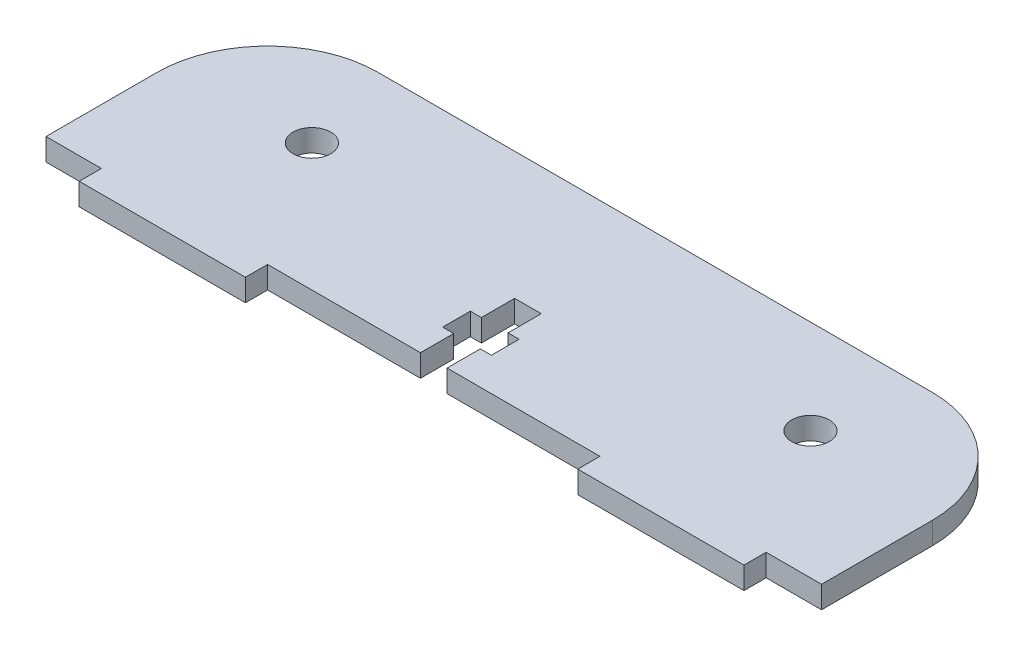
SolidWorks part; units mm, degrees
material "Thornel Mat VMA"
ref_plane "前视基准面" through (0, 0, 0) normal (0, 0, 1) x (1, 0, 0)
ref_plane "上视基准面" through (0, 0, 0) normal (0, 1, 0) x (1, 0, 0)
ref_plane "右视基准面" through (0, 0, 0) normal (1, 0, 0) x (0, 0, -1)
sketch "草图1" plane through (0, 0, 0) normal (0, 1, 0) x (1, 0, 0)
  line L1 (0, 0) -> (70, 0)
  line L2 (0, 0) -> (0, -20)
  line L3 (0, -20) -> (70, -20)
  line L4 (70, 0) -> (70, -20)
  line L5 (0, 0) -> (70, -20) construction
  line L6 (0, -20) -> (70, 0) construction
  circle A0 centre (57.5, -8.5) radius 1.7
  circle A1 centre (12.5, -8.5) radius 1.7
  point P4 (35, -10)
  dimension "D2" = 3.4
  dimension "D3" = 3.4
  dimension "D4" = 11.5
  dimension "D5" = 11.5
  dimension "D6" = 22.5
  dimension "D7" = 22.5
  dimension "D1" = 20
  dimension "D8" = 70
extrude "凸台-拉伸1" add sketch "草图1" along normal blind 2
sketch "草图2" plane through (0, 2, 0) normal (0, 1, 0) x (1, 0, 0)
  line L0 (33.8, -20) -> (33.8, -17)
  line L1 (0, -20) -> (70, -20) construction
  line L2 (33.8, -17) -> (32.8, -17)
  line L3 (32.8, -17) -> (32.8, -14.5)
  line L4 (32.8, -14.5) -> (33.8, -14.5)
  line L5 (33.8, -14.5) -> (33.8, -11.5)
  line L6 (33.8, -11.5) -> (36.2, -11.5)
  line L7 (36.2, -11.5) -> (36.2, -14.5)
  line L8 (36.2, -14.5) -> (37.2, -14.5)
  line L9 (37.2, -14.5) -> (37.2, -17)
  line L10 (37.2, -17) -> (36.2, -17)
  line L11 (36.2, -17) -> (36.2, -20)
  line L12 (33.8, -20) -> (36.2, -20)
  point P4 (35, -20)
  dimension "D1" = 2.4
  dimension "D2" = 1
  dimension "D3" = 1
  dimension "D4" = 2.4
  dimension "D5" = 1
  dimension "D6" = 3
  dimension "D7" = 3
  dimension "D8" = 3
  dimension "D9" = 2.5
  dimension "D10" = 2.5
  dimension "D11" = 1.2
extrude "切除-拉伸1" cut sketch "草图2" against normal blind 2
sketch "草图3" plane through (0, 2, 0) normal (0, 1, 0) x (1, 0, 0)
  line L0 (20, -20) -> (20, -22)
  line L1 (0, -20) -> (33.8, -20) construction
  line L2 (20, -22) -> (5, -22)
  line L3 (5, -22) -> (5, -20)
  line L4 (5, -20) -> (20, -20)
  line L5 (50, -20) -> (50, -22)
  line L6 (36.2, -20) -> (70, -20) construction
  line L7 (50, -22) -> (65, -22)
  line L8 (65, -22) -> (65, -20)
  line L9 (65, -20) -> (50, -20)
  line L11 (36.2, -11.5) -> (33.8, -11.5) construction
  point P14 (35, -11.5)
  dimension "D1" = 15
  dimension "D2" = 15
  dimension "D3" = 15
  dimension "D4" = 30
  dimension "D5" = 2
  dimension "D6" = 2
extrude "凸台-拉伸2" add sketch "草图3" against normal blind 2
fillet "圆角1" radius 10 2 edges at (0, 1, 0) (70, 1, 0)
